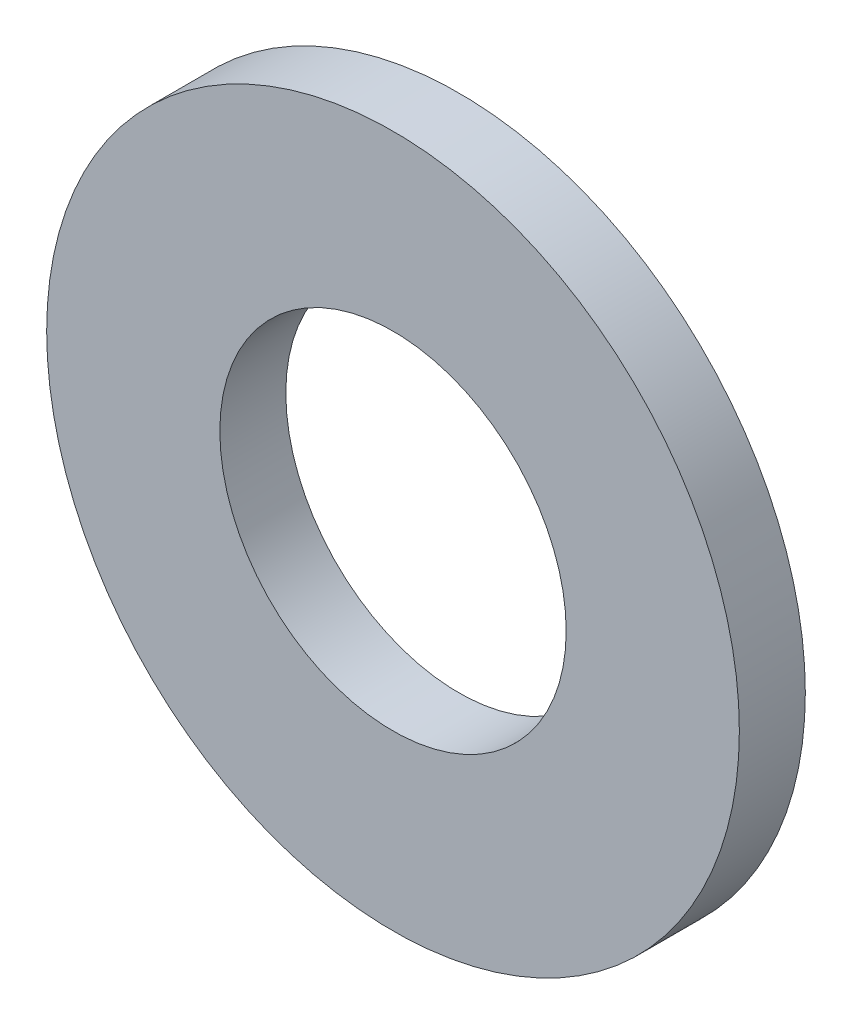
SolidWorks part; units mm, degrees
ref_plane "Спереди" through (0, 0, 0) normal (0, 0, 1) x (1, 0, 0)
ref_plane "Сверху" through (0, 0, 0) normal (0, 1, 0) x (1, 0, 0)
ref_plane "Справа" through (0, 0, 0) normal (1, 0, 0) x (0, 0, -1)
sketch "Эскиз1" plane through (0, 0, 0) normal (0, 0, 1) x (1, 0, 0)
  circle A0 centre (0, 0) radius 10.5
  circle A1 centre (0, 0) radius 5.25
  dimension "D1" = 21
  dimension "D2" = 10.5
extrude "Вытянуть1" add sketch "Эскиз1" along normal blind 2
